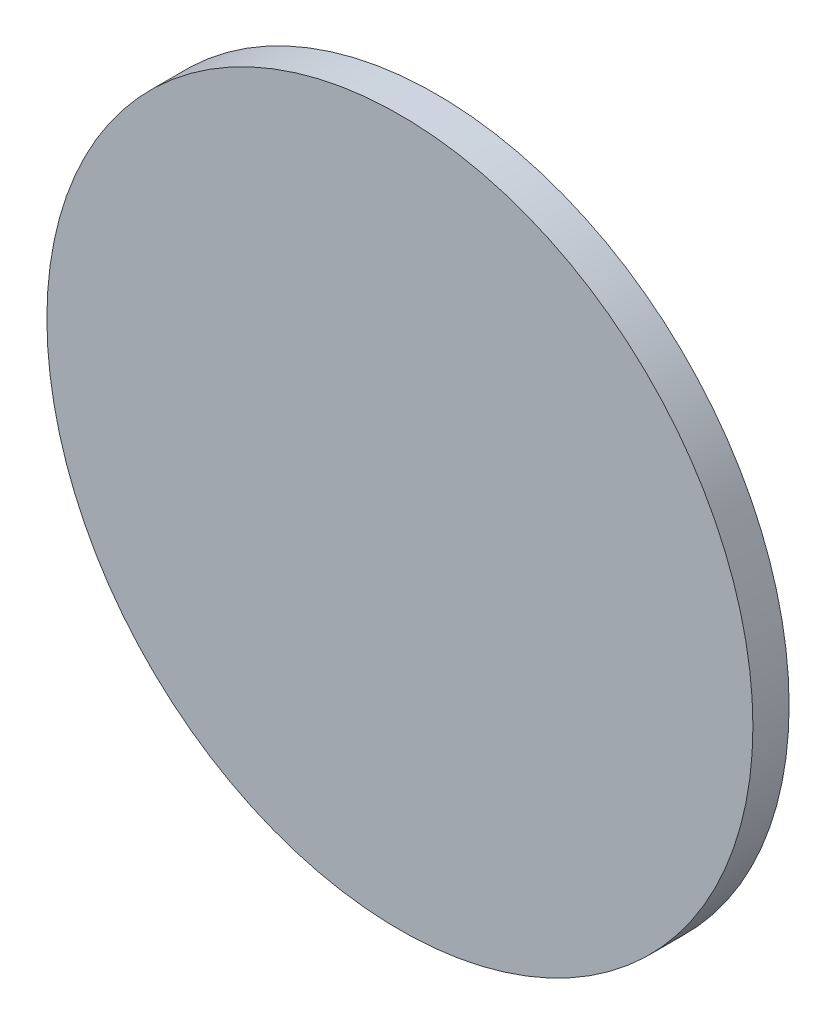
SolidWorks part; units mm, degrees
ref_plane "Front Plane" through (0, 0, 0) normal (0, 0, 1) x (1, 0, 0)
ref_plane "Top Plane" through (0, 0, 0) normal (0, 1, 0) x (1, 0, 0)
ref_plane "Right Plane" through (0, 0, 0) normal (1, 0, 0) x (0, 0, -1)
sketch "Sketch1" plane through (0, 0, 0) normal (0, 0, 1) x (1, 0, 0)
  circle A0 centre (0, 0) radius 19.5
  dimension "D1" = 39
extrude "Boss-Extrude1" add sketch "Sketch1" along normal blind 2
